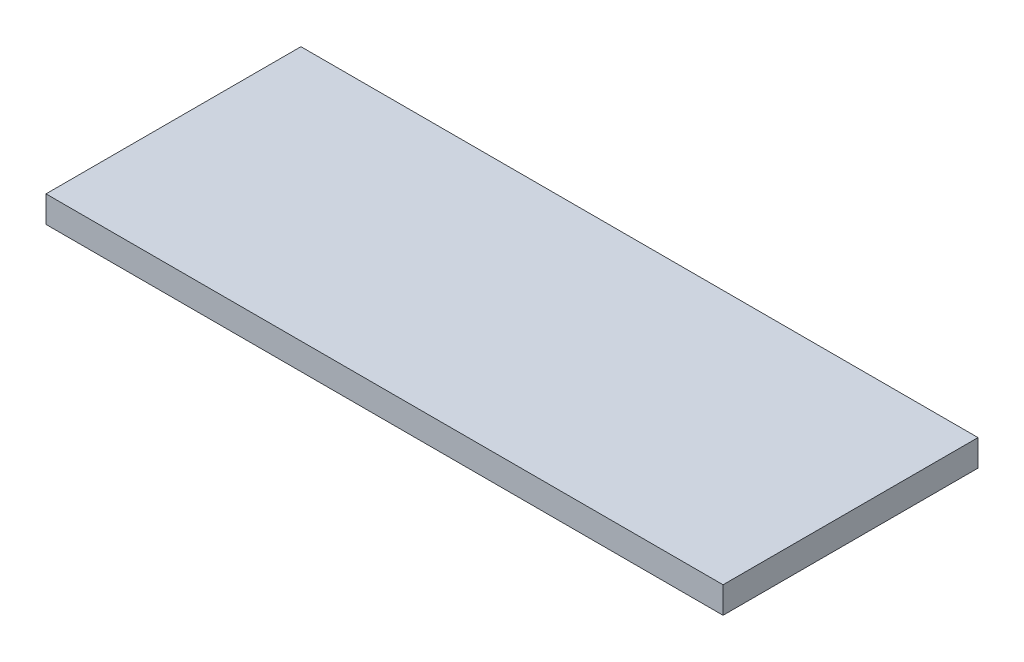
SolidWorks part; units mm, degrees
ref_plane "Front Plane" through (0, 0, 0) normal (0, 0, 1) x (1, 0, 0)
ref_plane "Top Plane" through (0, 0, 0) normal (0, 1, 0) x (1, 0, 0)
ref_plane "Right Plane" through (0, 0, 0) normal (1, 0, 0) x (0, 0, -1)
sketch "Sketch1" plane through (0, 0, 0) normal (0, 1, 0) x (1, 0, 0)
  line L0 (0, 7.7) -> (0, 0) construction
  line L1 (-20.45, 7.7) -> (20.45, 7.7)
  line L2 (-20.45, 7.7) -> (-20.45, -7.7)
  line L3 (-20.45, -7.7) -> (20.45, -7.7)
  line L4 (20.45, 7.7) -> (20.45, -7.7)
  line L5 (0, 0) -> (0, -7.7) construction
  dimension "D1" = 15.4
  dimension "D2" = 40.9
extrude "Boss-Extrude1" add sketch "Sketch1" along normal blind 1.6
